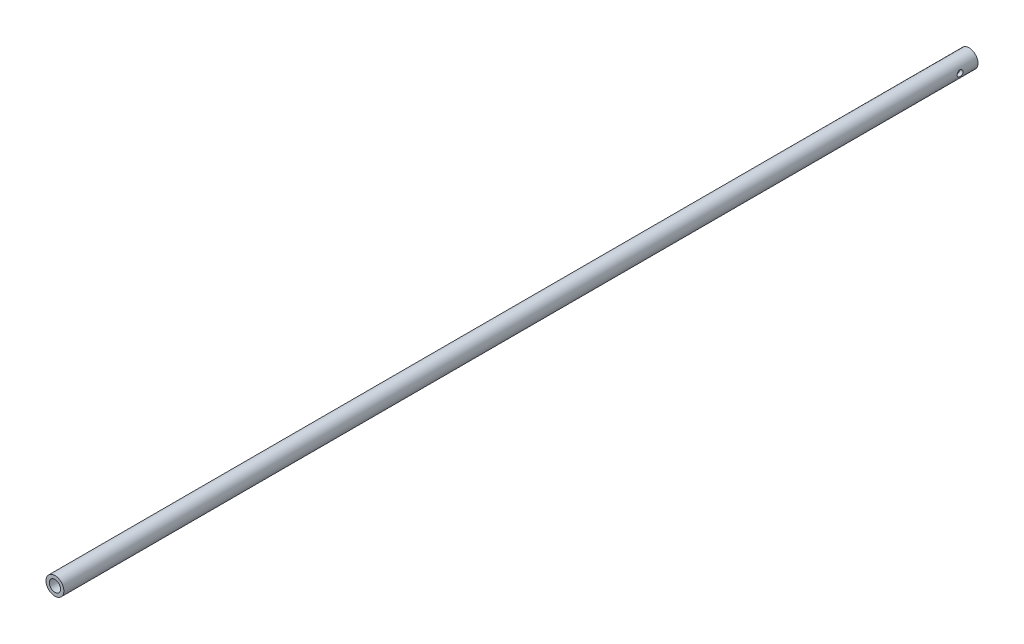
SolidWorks part; units mm, degrees
ref_plane "Front Plane" through (0, 0, 0) normal (0, 0, 1) x (1, 0, 0)
ref_plane "Top Plane" through (0, 0, 0) normal (0, 1, 0) x (1, 0, 0)
ref_plane "Right Plane" through (0, 0, 0) normal (1, 0, 0) x (0, 0, -1)
sketch "Sketch1" plane through (0, 0, 0) normal (0, 0, 1) x (1, 0, 0)
  circle A0 centre (0, 0) radius 2.3876
  circle A1 centre (0, 0) radius 1.4986
  dimension "D1" = 4.7752
  dimension "D2" = 2.9972
extrude "Boss-Extrude1" add sketch "Sketch1" along normal blind 243.84
sketch "Sketch2" plane through (0, 0, 0) normal (1, 0, 0) x (0, 0, -1)
  line L0 (0, 0) -> (-4.7625, 0) construction
  circle A0 centre (-4.7625, 0) radius 0.7938
  dimension "D1" = 1.5875
  dimension "D2" = 4.7625
extrude "Cut-Extrude1" cut sketch "Sketch2" against normal through all and the other way through all contours A0
